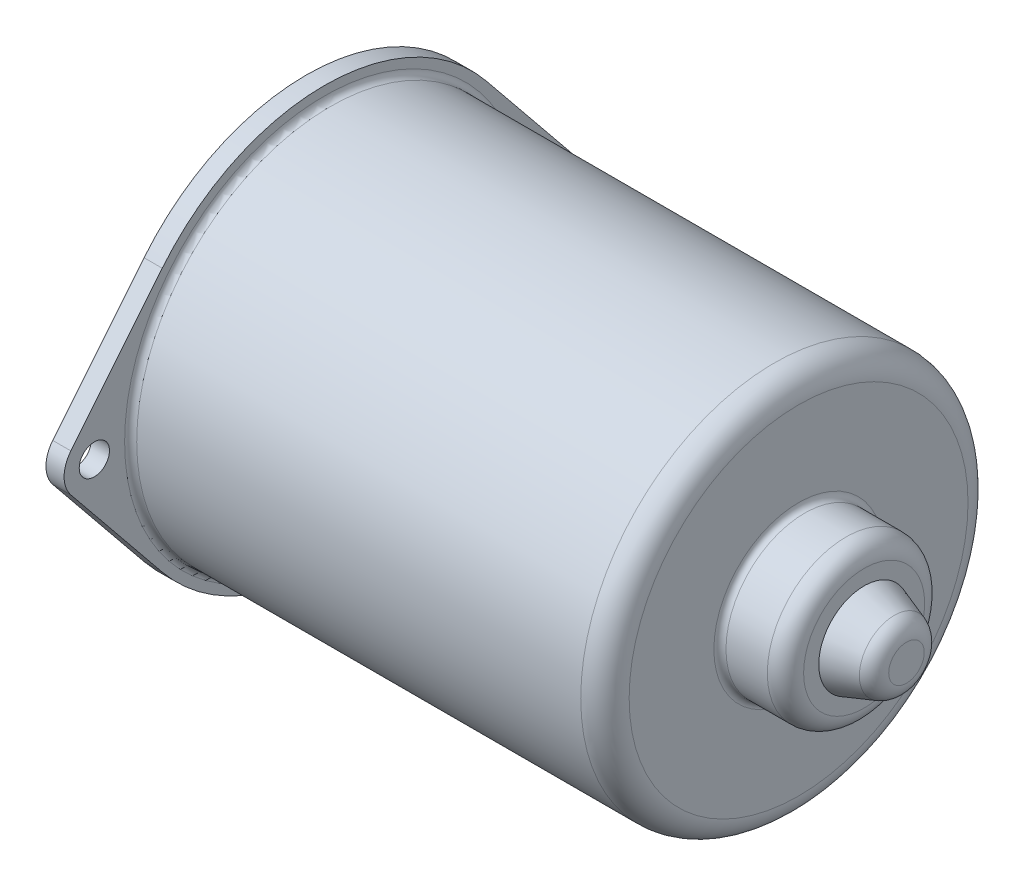
SolidWorks part; units mm, degrees
ref_plane "Plan de face" through (0, 0, 0) normal (0, 0, 1) x (1, 0, 0)
ref_plane "Plan de dessus" through (0, 0, 0) normal (0, 1, 0) x (1, 0, 0)
ref_plane "Plan de droite" through (0, 0, 0) normal (1, 0, 0) x (0, 0, -1)
sketch "Esquisse1" plane through (0, 0, 0) normal (0, 0, 1) x (1, 0, 0)
  line L0 (-73.1633, 0) -> (87.5422, 0) construction
  line L1 (-43.8416, 45) -> (-43.8416, 29)
  line L2 (-43.8416, 29) -> (33.5376, 29)
  line L3 (-43.8416, 45) -> (-40.8416, 45)
  line L4 (-40.8416, 45) -> (-40.8416, 33)
  line L5 (-39.8416, 32) -> (33.5376, 32)
  line L6 (34.5376, 28) -> (34.5376, 14)
  line L7 (37.5376, 28) -> (37.5376, 14)
  line L8 (38.5376, 13) -> (45.3703, 13)
  line L9 (48.3703, 10) -> (48.3703, 7.5)
  line L10 (38.5376, 10) -> (45.3703, 10)
  line L11 (45.3703, 10) -> (45.3703, 5.3654)
  line L12 (48.3703, 7.5) -> (53.3536, 5.7712)
  line L13 (55.3703, 2.9369) -> (55.3703, 0)
  line L14 (45.3703, 5.3654) -> (52.3703, 2.9369)
  line L15 (52.3703, 2.9369) -> (52.3703, 0)
  line L16 (52.3703, 0) -> (55.3703, 0)
  arc A0 (55.3703, 2.9369) -> (53.3536, 5.7712) centre (52.3703, 2.9369) ccw
  arc A1 (-39.8416, 32) -> (-40.8416, 33) centre (-39.8416, 33) cw
  arc A2 (38.5376, 13) -> (37.5376, 14) centre (38.5376, 14) cw
  arc A3 (37.5376, 28) -> (33.5376, 32) centre (33.5376, 28) ccw
  arc A4 (34.5376, 28) -> (33.5376, 29) centre (33.5376, 28) ccw
  arc A5 (38.5376, 10) -> (34.5376, 14) centre (38.5376, 14) cw
  arc A6 (48.3703, 10) -> (45.3703, 13) centre (45.3703, 10) ccw
  dimension "D9" = 3
  dimension "D12" = 1
  dimension "D13" = 4
  dimension "D14" = 1
  dimension "D15" = 4
  dimension "D16" = 3
  dimension "D1" = 3
  dimension "D2" = 3
  dimension "D3" = 3
  dimension "D4" = 90
  dimension "D5" = 64
  dimension "D6" = 3
  dimension "D7" = 3
  dimension "D8" = 26
  dimension "D10" = 7
  dimension "D11" = 15
revolve "Révolution1" add sketch "Esquisse1" angle 360 about L0
sketch "Esquisse2" plane through (-43.8416, 0, 0) normal (-1, 0, 0) x (0, 0, 1)
  line L0 (-52.3063, 0) -> (55.8118, 0) construction
  line L1 (-41.8816, 3.1517) -> (-26.7829, 21.7469)
  line L2 (26.7829, 21.7469) -> (41.8816, 3.1517)
  line L4 (-26.7829, -21.7469) -> (-41.8816, -3.1517)
  line L5 (41.8816, -3.1517) -> (26.7829, -21.7469)
  arc A2 (26.7829, 21.7469) -> (-26.7829, 21.7469) centre (0, 0) ccw
  arc A3 (-26.7829, -21.7469) -> (26.7829, -21.7469) centre (0, 0) ccw
  arc A4 (-41.8816, 3.1517) -> (-41.8816, -3.1517) centre (-38, 0) ccw
  arc A5 (41.8816, -3.1517) -> (41.8816, 3.1517) centre (38, 0) ccw
  circle A6 centre (0, 0) radius 49.0658
  dimension "D5" = 69
  dimension "D1" = 38
extrude "Enlèv. mat.-Extru.1" cut sketch "Esquisse2" against normal through all
sketch "Esquisse3" plane through (-43.8416, 0, 0) normal (-1, 0, 0) x (0, 0, 1)
  circle A0 centre (38, 0) radius 2.5
  circle A1 centre (-38, 0) radius 2.5
  dimension "D1" = 5
  dimension "D2" = 5
extrude "Enlèv. mat.-Extru.2" cut sketch "Esquisse3" against normal through all
